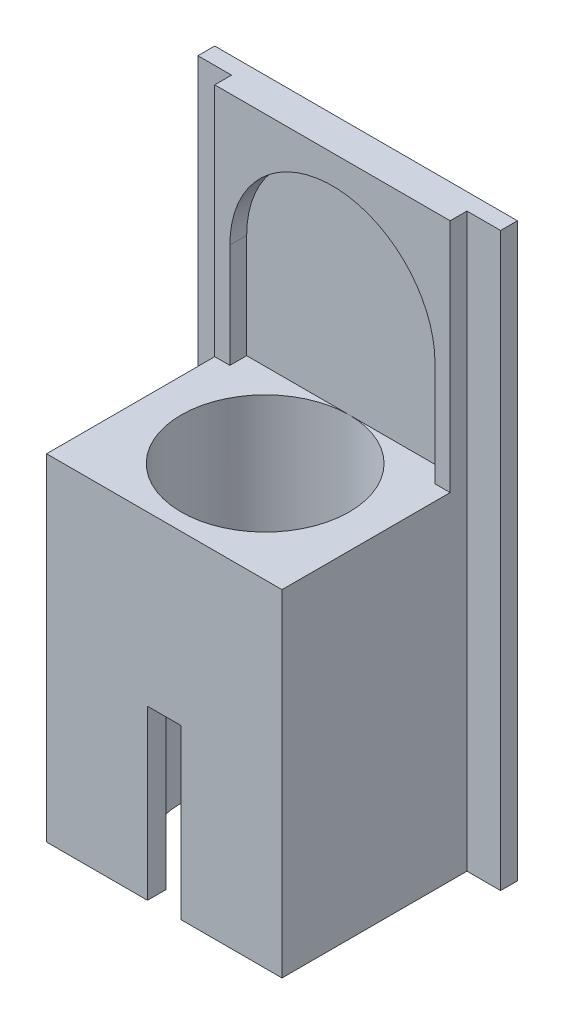
SolidWorks part; units mm, degrees
ref_plane "Plan de face" through (0, 0, 0) normal (0, 0, 1) x (1, 0, 0)
ref_plane "Plan de dessus" through (0, 0, 0) normal (0, 1, 0) x (1, 0, 0)
ref_plane "Plan de droite" through (0, 0, 0) normal (1, 0, 0) x (0, 0, -1)
sketch "Esquisse1" plane through (0, 0, 0) normal (0, 0, 1) x (1, 0, 0)
  line L1 (-755.518, -500.7692) -> (-665.518, -500.7692)
  line L2 (-755.518, -500.7692) -> (-755.518, -670.7692)
  line L3 (-755.518, -670.7692) -> (-665.518, -670.7692)
  line L4 (-665.518, -500.7692) -> (-665.518, -670.7692)
  dimension "D1" = 170
  dimension "D2" = 90
extrude "Boss.-Extru.1" add sketch "Esquisse1" along normal blind 5
sketch "Esquisse2" plane through (0, 0, 5) normal (0, 0, 1) x (1, 0, 0)
  line L1 (-665.518, -500.7692) -> (-755.518, -500.7692) construction
  line L2 (-745.518, -670.7692) -> (-675.518, -670.7692)
  line L3 (-745.518, -670.7692) -> (-745.518, -570.7692)
  line L4 (-745.518, -570.7692) -> (-675.518, -570.7692)
  line L6 (-675.518, -670.7692) -> (-675.518, -570.7692)
  line L7 (-755.518, -500.7692) -> (-755.518, -670.7692) construction
  line L8 (-665.518, -670.7692) -> (-665.518, -500.7692) construction
  line L9 (-755.518, -670.7692) -> (-665.518, -670.7692) construction
  dimension "D1" = 70
  dimension "D2" = 10
  dimension "D3" = 10
  dimension "D4" = 0
extrude "Boss.-Extru.2" add sketch "Esquisse2" along normal blind 55
sketch "Esquisse4" plane through (0, -570.7692, 0) normal (0, 1, 0) x (1, 0, 0)
  line L0 (-675.518, -5) -> (-745.518, -5) construction
  line L1 (-745.518, -60) -> (-745.518, -5) construction
  line L2 (-675.518, -60) -> (-675.518, -5) construction
  circle A0 centre (-710.518, -30) radius 25
  dimension "D1" = 50
  dimension "D2" = 25
  dimension "D3" = 35
  dimension "D4" = 35
extrude "Enlèv. mat.-Extru.2" cut sketch "Esquisse4" against normal up to next
sketch "Esquisse5" plane through (0, 0, 60) normal (0, 0, 1) x (1, 0, 0)
  line L0 (-745.518, -670.7692) -> (-675.518, -670.7692) construction
  line L1 (-705.518, -620.7692) -> (-715.518, -620.7692)
  line L2 (-705.518, -620.7692) -> (-705.518, -670.7692)
  line L3 (-705.518, -670.7692) -> (-715.518, -670.7692)
  line L4 (-715.518, -620.7692) -> (-715.518, -670.7692)
  line L5 (-745.518, -570.7692) -> (-745.518, -670.7692) construction
  point P6 (-735.5982, -628.7397)
  dimension "D1" = 10
  dimension "D2" = 50
  dimension "D3" = 30
extrude "Enlèv. mat.-Extru.3" cut sketch "Esquisse5" against normal up to next
sketch "Esquisse6" plane through (0, 0, 5) normal (0, 0, 1) x (1, 0, 0)
  line L0 (-755.518, -500.7692) -> (-755.518, -670.7692) construction
  line L1 (-745.518, -500.7692) -> (-675.518, -500.7692)
  line L2 (-745.518, -500.7692) -> (-745.518, -570.7692)
  line L3 (-745.518, -570.7692) -> (-675.518, -570.7692)
  line L4 (-675.518, -500.7692) -> (-675.518, -570.7692)
  line L5 (-665.518, -500.7692) -> (-755.518, -500.7692) construction
  dimension "D1" = 70
  dimension "D2" = 70
  dimension "D3" = 10
  dimension "D4" = 0
extrude "Boss.-Extru.3" add sketch "Esquisse6" along normal blind 5
sketch "Esquisse7" plane through (0, 0, 10) normal (0, 0, 1) x (1, 0, 0)
  line L0 (-745.518, -500.7692) -> (-745.518, -570.7692) construction
  line L2 (-741.018, -539.7692) -> (-741.018, -570.7692)
  line L3 (-741.018, -570.7692) -> (-680.018, -570.7692)
  line L4 (-680.018, -539.7692) -> (-680.018, -570.7692)
  line L5 (-695.518, -570.7692) -> (-675.518, -570.7692) construction
  line L6 (-675.518, -570.7692) -> (-675.518, -500.7692) construction
  arc A0 (-741.018, -539.7692) -> (-680.018, -539.7692) centre (-710.518, -539.7692) cw
  dimension "D1" = 61
  dimension "D2" = 31
  dimension "D3" = 4.5
  dimension "D4" = 0
  dimension "D5" = 4.5
extrude "Enlèv. mat.-Extru.4" cut sketch "Esquisse7" against normal blind 5
